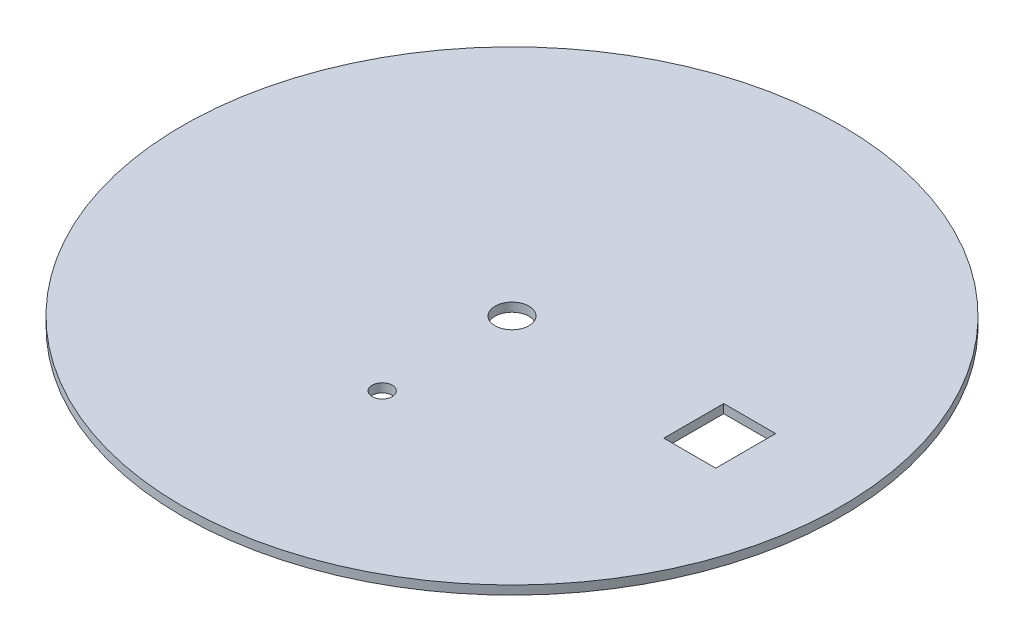
SolidWorks part; units mm, degrees
ref_plane "Front Plane" through (0, 0, 0) normal (0, 0, 1) x (1, 0, 0)
ref_plane "Top Plane" through (0, 0, 0) normal (0, 1, 0) x (1, 0, 0)
ref_plane "Right Plane" through (0, 0, 0) normal (1, 0, 0) x (0, 0, -1)
sketch "Sketch1" plane through (0, 0, 0) normal (0, 1, 0) x (1, 0, 0)
  circle A0 centre (0, 0) radius 16.5
extrude "Boss-Extrude1" add sketch "Sketch1" along normal blind 0.44
sketch "Sketch2" plane through (0, 0.44, 0) normal (0, 1, 0) x (1, 0, 0)
  circle A0 centre (0, 0) radius 0.85
extrude "Cut-Extrude1" cut sketch "Sketch2" against normal blind 0.44
sketch "Sketch3" plane through (0, 0.44, 0) normal (0, 1, 0) x (1, 0, 0)
  line L1 (9.1, -1.5) -> (9.1, 1.5)
  line L2 (9.1, 1.5) -> (11.7, 1.5)
  line L3 (11.7, 1.5) -> (11.7, -1.5)
  line L4 (11.7, -1.5) -> (9.1, -1.5)
  circle A0 centre (0, -6.5) radius 0.5
  point P0 (0, 0)
extrude "Cut-Extrude4" cut sketch "Sketch3" against normal blind 0.44
